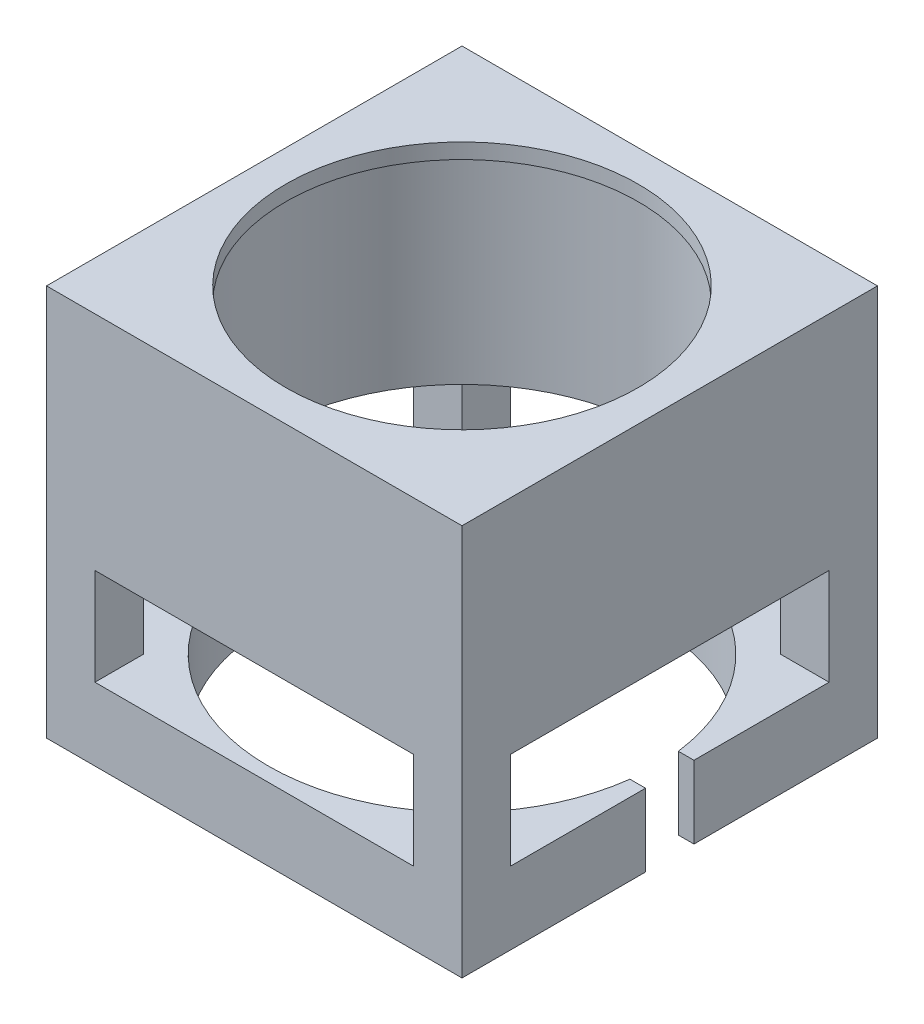
SolidWorks part; units mm, degrees
ref_plane "Front Plane" through (0, 0, 0) normal (0, 0, 1) x (1, 0, 0)
ref_plane "Top Plane" through (0, 0, 0) normal (0, 1, 0) x (1, 0, 0)
ref_plane "Right Plane" through (0, 0, 0) normal (1, 0, 0) x (0, 0, -1)
sketch "Sketch1" plane through (0, 0, 0) normal (0, 1, 0) x (1, 0, 0)
  line L1 (-109, -109) -> (109, -109)
  line L2 (-109, -109) -> (-109, 109)
  line L3 (-109, 109) -> (109, 109)
  line L4 (109, -109) -> (109, 109)
  line L5 (-109, -109) -> (109, 109) construction
  line L6 (-109, 109) -> (109, -109) construction
  circle A0 centre (0, 0) radius 101.6
  point P0 (0, 0)
  dimension "D3" = 203.2
  dimension "D1" = 218
  dimension "D2" = 218
extrude "Boss-Extrude1" add sketch "Sketch1" along normal blind 38.1
sketch "Sketch2" plane through (0, 38.1, 0) normal (0, 1, 0) x (1, 0, 0)
  line L1 (-109, 109) -> (-83.6, 109)
  line L2 (-109, 109) -> (-109, 83.6)
  line L3 (-109, 83.6) -> (-83.6, 83.6)
  line L4 (-83.6, 109) -> (-83.6, 83.6)
  line L5 (109, 109) -> (83.6, 109)
  line L6 (109, 109) -> (109, 83.6)
  line L7 (109, 83.6) -> (83.6, 83.6)
  line L8 (83.6, 109) -> (83.6, 83.6)
  line L9 (109, -109) -> (83.6, -109)
  line L10 (109, -109) -> (109, -83.6)
  line L11 (109, -83.6) -> (83.6, -83.6)
  line L12 (83.6, -109) -> (83.6, -83.6)
  line L13 (-109, -109) -> (-83.6, -109)
  line L14 (-109, -109) -> (-109, -83.6)
  line L15 (-109, -83.6) -> (-83.6, -83.6)
  line L16 (-83.6, -109) -> (-83.6, -83.6)
  dimension "D1" = 25.4
  dimension "D2" = 25.4
  dimension "D3" = 25.4
  dimension "D4" = 25.4
  dimension "D5" = 25.4
  dimension "D6" = 25.4
  dimension "D7" = 25.4
  dimension "D8" = 25.4
extrude "Boss-Extrude2" add sketch "Sketch2" along normal blind 50.8
sketch "Sketch3" plane through (0, 88.9, 0) normal (0, 1, 0) x (1, 0, 0)
  line L1 (-109, 109) -> (109, 109)
  line L2 (-109, 109) -> (-109, -109)
  line L3 (-109, -109) -> (109, -109)
  line L4 (109, 109) -> (109, -109)
  circle A0 centre (0, 0) radius 101.6
  dimension "D1" = 203.2
extrude "Boss-Extrude3" add sketch "Sketch3" along normal blind 108.6
sketch "Sketch4" plane through (0, 197.5, 0) normal (0, 1, 0) x (1, 0, 0)
  line L1 (-109, 109) -> (109, 109)
  line L2 (-109, 109) -> (-109, -109)
  line L3 (-109, -109) -> (109, -109)
  line L4 (109, 109) -> (109, -109)
  circle A0 centre (0, 0) radius 92.5
  dimension "D1" = 185
extrude "Boss-Extrude4" add sketch "Sketch4" along normal blind 8
sketch "Sketch5" plane through (0, 0, 0) normal (0, -1, 0) x (1, 0, 0)
  line L0 (109, 109) -> (109, -109) construction
  line L1 (117.1969, -12.7) -> (100.8031, -12.7)
  line L2 (117.1969, -12.7) -> (117.1969, 12.7)
  line L3 (117.1969, 12.7) -> (100.8031, 12.7)
  line L4 (100.8031, -12.7) -> (100.8031, 12.7)
  line L5 (117.1969, -12.7) -> (100.8031, 12.7) construction
  line L6 (117.1969, 12.7) -> (100.8031, -12.7) construction
  circle A0 centre (0, 0) radius 101.6 construction
  point P0 (109, 0)
  dimension "D1" = 25.4
extrude "Cut-Extrude1" cut sketch "Sketch5" against normal up to next
